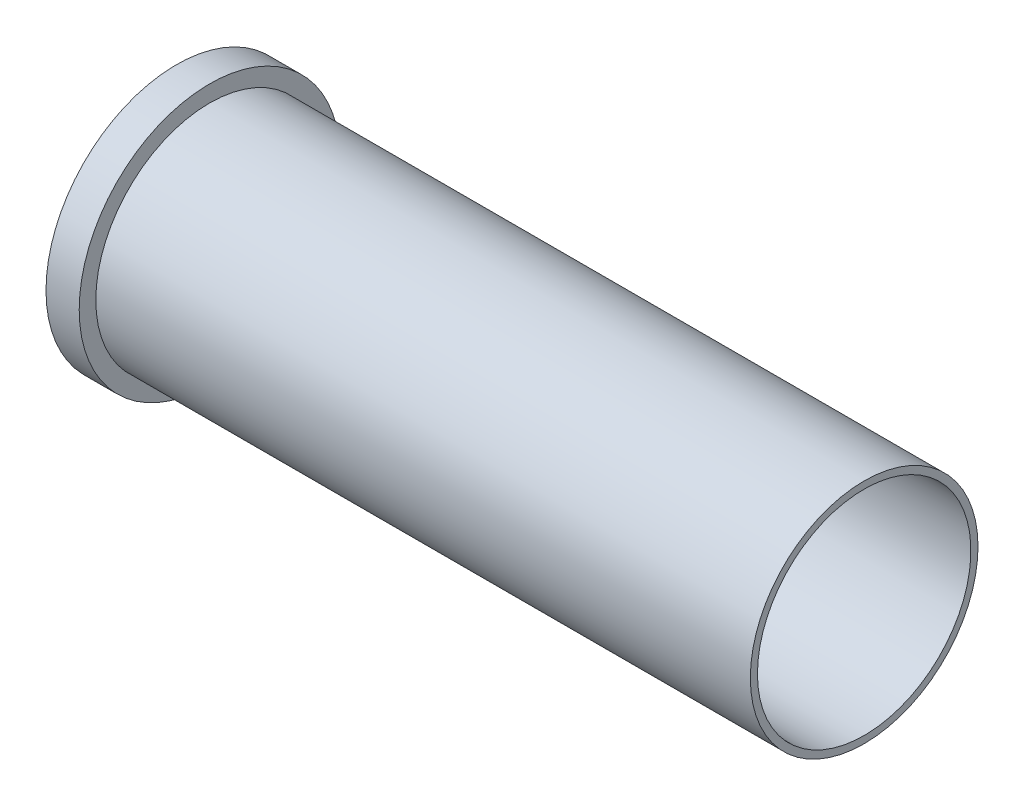
SolidWorks part; units mm, degrees
ref_plane "Plano frontal" through (0, 0, 0) normal (0, 0, 1) x (1, 0, 0)
ref_plane "Plano superior" through (0, 0, 0) normal (0, 1, 0) x (1, 0, 0)
ref_plane "Plano direito" through (0, 0, 0) normal (1, 0, 0) x (0, 0, -1)
sketch "Esboço1" plane through (0, 0, 0) normal (0, 1, 0) x (1, 0, 0)
  line L0 (0, 0) -> (31.341, 0) construction
  line L4 (3, 1.1) -> (3, 2.25)
  line L5 (3, 2.25) -> (0, 2.25)
  line L6 (0, 2.25) -> (0, 5.5)
  line L7 (0, 5.5) -> (1.4, 5.5)
  line L8 (1.4, 5.5) -> (1.4, 4.8)
  line L9 (1.4, 4.8) -> (29, 4.8)
  line L10 (29, 4.8) -> (29, 4.5)
  line L11 (29, 4.5) -> (3.8, 4.5)
  line L12 (3.8, 4.5) -> (3.8, 1.1)
  line L13 (3.8, 1.1) -> (3, 1.1)
  point P6 (16.0519, 3.3193)
  point P16 (0, 3.3193)
  dimension "D1" = 5.5
  dimension "D2" = 1.4
  dimension "D3" = 27.6
  dimension "D4" = 0.3
  dimension "D5" = 1.1
  dimension "D6" = 3
  dimension "D7" = 3.8
  dimension "D8" = 3.25
  dimension "D9" = 0.7
  dimension "D10" = 29
  dimension "D11" = 1.15
revolve "Revolução1" add sketch "Esboço1" angle 360 about L0
